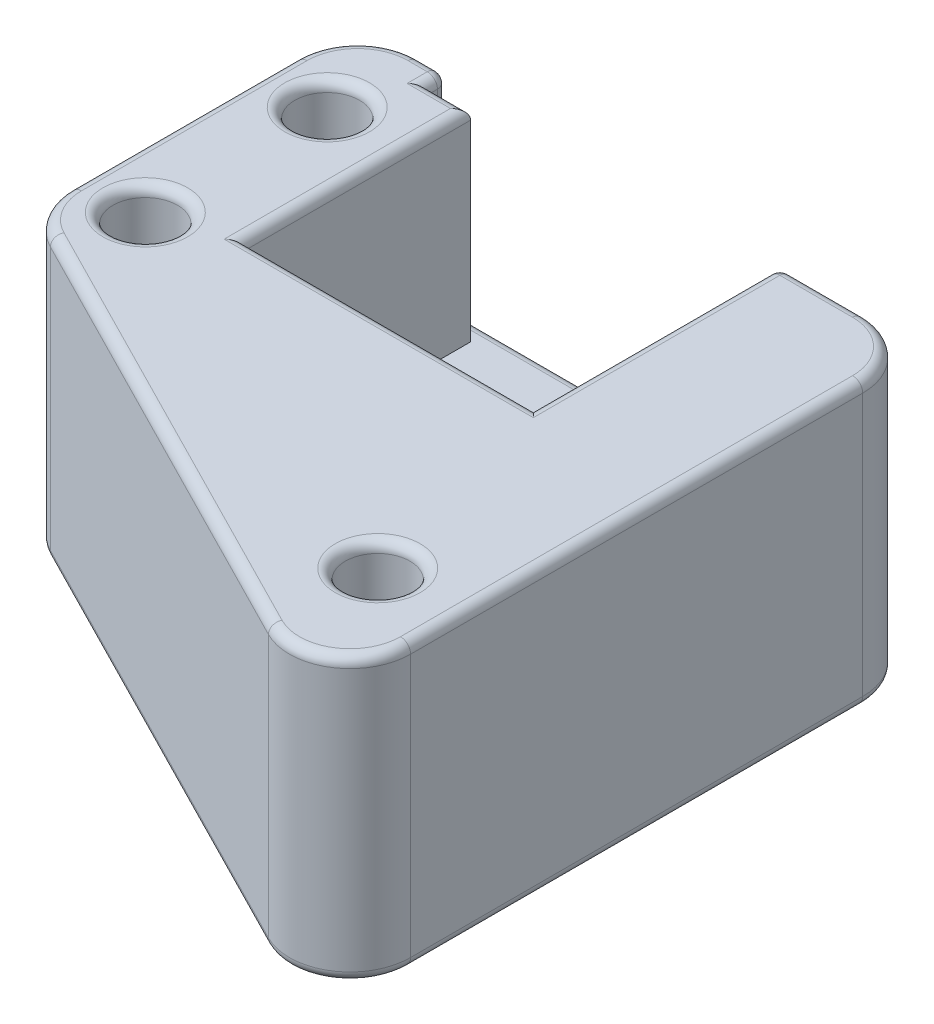
SolidWorks part; units mm, degrees
ref_plane "Front Plane" through (0, 0, 0) normal (0, 0, 1) x (1, 0, 0)
ref_plane "Top Plane" through (0, 0, 0) normal (0, 1, 0) x (1, 0, 0)
ref_plane "Right Plane" through (0, 0, 0) normal (1, 0, 0) x (0, 0, -1)
sketch "Sketch1" plane through (0, 0, 0) normal (0, 1, 0) x (1, 0, 0)
  line L0 (-3.25, 0) -> (3.25, 0) construction
  line L1 (6.4, 5) -> (-6.4, 5) construction
  line L2 (-14, -10) -> (14, -10)
  line L3 (-14, -10) -> (-14, 6)
  line L4 (-14, 6) -> (14, 6)
  line L5 (14, -10) -> (14, 6)
  line L6 (-11, -7.5) -> (10, -7.5) construction
  line L7 (0, 0) -> (0, -10) construction
  line L8 (-11, -7.5) -> (-11, 1.5) construction
  line L9 (-11, 1.5) -> (10, 1.5) construction
  line L10 (10, 1.5) -> (10, -7.5) construction
  circle A0 centre (3.25, 0) radius 0.85
  circle A1 centre (-3.25, 0) radius 0.85
  circle A2 centre (-11, -7.5) radius 1.6
  circle A3 centre (10, -7.5) radius 1.6 construction
  circle A4 centre (-11, -7.5) radius 3 construction
  circle A5 centre (-11, 1.5) radius 1.6
  circle A6 centre (10, 1.5) radius 1.6 construction
  circle A7 centre (-11, 1.5) radius 3 construction
  point P4 (0, 0)
  dimension "D1" = 1.7
  dimension "D2" = 6.5
  dimension "D6" = 3.2
  dimension "D8" = 6
  dimension "D9" = 9
  dimension "D10" = 2.5
  dimension "D3" = 16
  dimension "D4" = 28
  dimension "D5" = 1
  dimension "D7" = 21
  dimension "D11" = 4
extrude "Boss-Extrude1" add sketch "Sketch1" along normal blind 4
sketch "Sketch2" plane through (0, 4, 0) normal (0, 1, 0) x (1, 0, 0)
  line L0 (-9.5462, 6) -> (-9.5462, 5)
  line L1 (-7.4, -6.2) -> (6.9, -6.2)
  line L2 (6.9, -6.2) -> (6.9, 6)
  line L3 (-9.5462, 6) -> (-14, 6)
  line L4 (-14, 6) -> (-14, -10)
  line L5 (-14, -10) -> (14, -10)
  line L6 (14, -10) -> (14, 6)
  line L7 (14, 6) -> (6.9, 6)
  line L8 (14, -10) -> (14, 6) construction
  line L9 (14, 6) -> (-14, 6) construction
  line L10 (6.4, 1.3) -> (6.4, 5) construction
  line L11 (-14, 6) -> (-14, -10) construction
  line L13 (4.75, -1.2) -> (6.4, -1.2) construction
  line L14 (-9.5462, 5) -> (-7.4, 5)
  line L15 (-7.4, 5) -> (-7.4, -6.2)
  line L16 (-6.4, 5) -> (6.4, 5) construction
  line L17 (-6.4, 5) -> (-6.4, 1.3) construction
  circle A0 centre (-11, -7.5) radius 1.6 construction
  circle A1 centre (-11, -7.5) radius 1.6
  circle A5 centre (-11, 1.5) radius 1.6 construction
  circle A7 centre (-11, 1.5) radius 1.6
  dimension "D1" = 0.5
  dimension "D2" = 5
  dimension "D3" = 2
  dimension "D4" = 1
extrude "Boss-Extrude2" add sketch "Sketch2" along normal blind 10
sketch "Sketch4" plane through (0, 0, 0) normal (0, -1, 0) x (1, 0, 0)
  line L0 (14, 10) -> (14, 24.2667)
  line L1 (14, 24.2667) -> (-14, 10)
  line L2 (10, 17) -> (10, 7.5) construction
  line L3 (14, 10) -> (-14, 10)
  line L4 (-11, 7.5) -> (10, 7.5) construction
  circle A0 centre (10, 17) radius 1.6
  circle A2 centre (-11, 7.5) radius 1.6 construction
  dimension "D1" = 9.5
  dimension "D3" = 3.2
  dimension "D2" = 27
  dimension "D4" = 21
extrude "Boss-Extrude3" add sketch "Sketch4" against normal through all
fillet "Fillet2" radius 3 4 edges at (-14, 7, -6) (14, 7, -6) (-14, 7, 10) (14, 7, 24.2667)
fillet "Fillet1" radius 0.5 33 edges at (-3.25, 0, 0.85) (-14, 0, 2.5808) (14, 0, 8.1856) (3.25, 0, 0.85) (-11, 0, 9.1) (6.9, 9, -6) (-1.3231, 4, -6) (-9.5462, 9, -6) (0, 0, -6) (-9.5462, 14, -5.5) (-8.4731, 14, -5) (-7.4, 14, 0.6) (-0.25, 14, 6.2) (6.9, 14, 0.1) (8.95, 14, -6) (14, 14, 8.1856) (-14, 14, 2.5808) (-10.2731, 14, -6) (-11, 14, 9.1) (-11, 0, 0.1) (-11, 14, 0.1) (10, 0, 15.4) (-1.362, 14, 16.4394) (-1.362, 0, 16.4394) (10, 14, 15.4) (-13.5579, 0, 9.7291) (12.5675, 0, 21.9291) (13.1213, 0, -5.1213) (-13.1213, 0, -5.1213) (13.1213, 14, -5.1213) (12.5675, 14, 21.9291) (-13.5579, 14, 9.7291) (-13.1213, 14, -5.1213)
